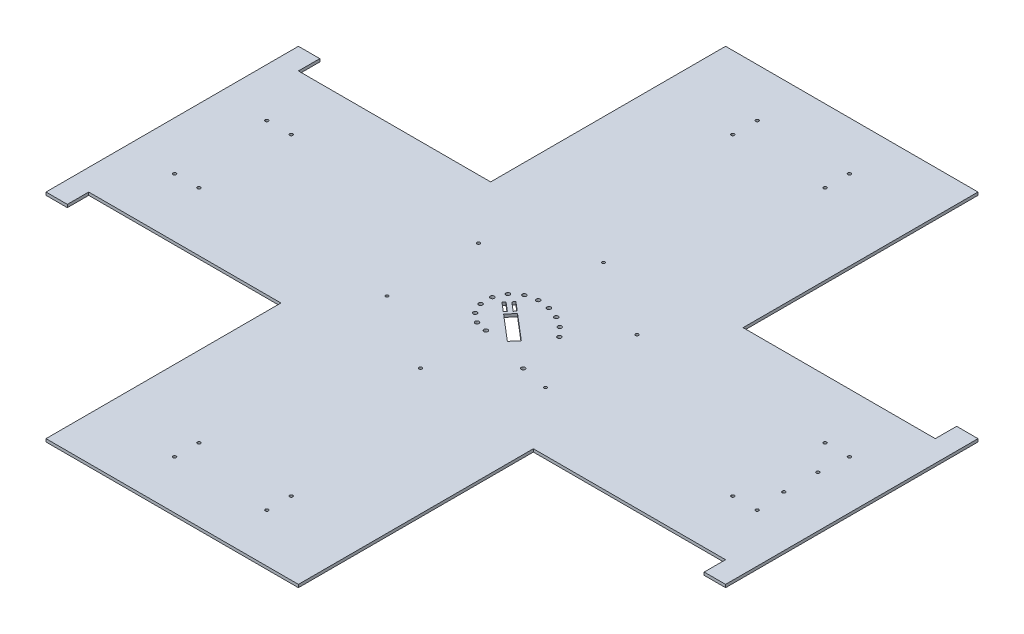
SolidWorks part; units mm, degrees
ref_plane "Front Plane" through (0, 0, 0) normal (0, 0, 1) x (1, 0, 0)
ref_plane "Top Plane" through (0, 0, 0) normal (0, 1, 0) x (1, 0, 0)
ref_plane "Right Plane" through (0, 0, 0) normal (1, 0, 0) x (0, 0, -1)
sketch "Sketch1" plane through (0, 0, 0) normal (0, 1, 0) x (1, 0, 0)
  line L0 (-350, -130) -> (-328, -130)
  line L1 (-130, -350) -> (130, -350)
  line L2 (-350, -130) -> (-350, 130)
  line L3 (-130, 350) -> (130, 350)
  line L4 (350, -130) -> (350, 130)
  line L7 (-350, 350) -> (-130, 350) construction
  line L8 (-350, 350) -> (-350, 130) construction
  line L9 (-350, 130) -> (-328, 130)
  line L10 (-130, 350) -> (-130, 130)
  line L11 (-350, 350) -> (-130, 130) construction
  line L12 (-350, 130) -> (-130, 350) construction
  line L13 (-350, -130) -> (-350, -350) construction
  line L14 (-350, -350) -> (-130, -350) construction
  line L15 (-130, -130) -> (-130, -350)
  line L16 (-350, -130) -> (-130, -350) construction
  line L17 (-350, -350) -> (-130, -130) construction
  line L18 (130, 350) -> (350, 350) construction
  line L19 (130, 350) -> (130, 130)
  line L20 (328, 130) -> (350, 130)
  line L21 (350, 350) -> (350, 130) construction
  line L22 (130, 350) -> (350, 130) construction
  line L23 (130, 130) -> (350, 350) construction
  line L24 (328, -130) -> (350, -130)
  line L25 (130, -130) -> (130, -350)
  line L26 (130, -350) -> (350, -350) construction
  line L27 (350, -130) -> (350, -350) construction
  line L28 (130, -130) -> (350, -350) construction
  line L29 (130, -350) -> (350, -130) construction
  line L30 (-328, -108) -> (-130, -108)
  line L31 (-328, 130) -> (-130, 130) construction
  line L32 (-328, 130) -> (-328, 108)
  line L33 (-328, 108) -> (-130, 108)
  line L34 (-130, 130) -> (-130, 108)
  line L35 (-328, 130) -> (-130, 108) construction
  line L36 (-328, 108) -> (-130, 130) construction
  line L37 (-328, -108) -> (-328, -130)
  line L38 (-328, -130) -> (-130, -130) construction
  line L39 (-130, -108) -> (-130, -130)
  line L40 (-328, -108) -> (-130, -130) construction
  line L41 (-328, -130) -> (-130, -108) construction
  line L42 (130, 130) -> (328, 130) construction
  line L43 (130, 130) -> (130, 108)
  line L44 (130, 108) -> (328, 108)
  line L45 (328, 130) -> (328, 108)
  line L46 (130, 130) -> (328, 108) construction
  line L47 (130, 108) -> (328, 130) construction
  line L48 (130, -108) -> (328, -108)
  line L49 (130, -108) -> (130, -130)
  line L50 (130, -130) -> (328, -130) construction
  line L51 (328, -108) -> (328, -130)
  line L52 (130, -108) -> (328, -130) construction
  line L53 (130, -130) -> (328, -108) construction
  line L54 (-130, 350) -> (130, -350) construction
  point P0 (0, 0)
  point P1 (0, 0)
  point P10 (-240, 240)
  point P15 (-240, -240)
  point P20 (240, 240)
  point P25 (240, -240)
  point P30 (-229, 119)
  point P35 (-229, -119)
  point P40 (229, 119)
  point P45 (229, -119)
  dimension "D3" = 220
  dimension "D4" = 220
  dimension "D5" = 220
  dimension "D6" = 220
  dimension "D7" = 220
  dimension "D8" = 220
  dimension "D9" = 220
  dimension "D10" = 220
  dimension "D11" = 22
  dimension "D12" = 198
  dimension "D13" = 22
  dimension "D14" = 198
  dimension "D15" = 22
  dimension "D16" = 198
  dimension "D17" = 22
  dimension "D18" = 198
extrude "Boss-Extrude1" add sketch "Sketch1" along normal blind 3
sketch "Sketch2" plane through (0, 3, 0) normal (0, 1, 0) x (1, 0, 0)
  line L0 (-300, 108) -> (-300, 47.5) construction
  line L1 (-130, 108) -> (-328, 108) construction
  line L2 (-300, -47.5) -> (-300, -108) construction
  line L3 (-328, -108) -> (-130, -108) construction
  line L4 (-300, 47.5) -> (-300, -47.5) construction
  line L5 (-47.5, 300) -> (-130, 300) construction
  line L6 (-130, 350) -> (-130, 108) construction
  line L7 (-47.5, 300) -> (47.5, 300) construction
  line L8 (47.5, 300) -> (130, 300) construction
  line L9 (130, 108) -> (130, 350) construction
  line L10 (130, 350) -> (-130, 350) construction
  line L11 (-350, 130) -> (-350, -130) construction
  line L12 (-130, -300) -> (-47.5, -300) construction
  line L13 (-130, -108) -> (-130, -350) construction
  line L14 (-47.5, -300) -> (47.5, -300) construction
  line L15 (47.5, -300) -> (130, -300) construction
  line L16 (130, -350) -> (130, -108) construction
  line L17 (-130, -350) -> (130, -350) construction
  line L18 (300, 108) -> (300, 47.5) construction
  line L19 (328, 108) -> (130, 108) construction
  line L20 (300, 47.5) -> (300, -47.5) construction
  line L21 (300, -47.5) -> (300, -108) construction
  line L22 (130, -108) -> (328, -108) construction
  line L23 (350, -130) -> (350, 130) construction
  line L24 (300, 47.5) -> (275, 47.5) construction
  line L25 (-47.5, -300) -> (-47.5, -275) construction
  line L26 (297.5, 17.5) -> (297.5, -17.5) construction
  circle A0 centre (-300, 47.5) radius 1.6
  circle A1 centre (-300, -47.5) radius 1.6
  circle A2 centre (-47.5, 300) radius 1.6
  circle A3 centre (47.5, 300) radius 1.6
  circle A4 centre (-47.5, -300) radius 1.6
  circle A5 centre (47.5, -300) radius 1.6
  circle A6 centre (300, 47.5) radius 1.6
  circle A7 centre (300, -47.5) radius 1.6
  circle A8 centre (-275, 47.5) radius 1.6
  circle A9 centre (-275, -47.5) radius 1.6
  circle A10 centre (-47.5, 275) radius 1.6
  circle A11 centre (47.5, 275) radius 1.6
  circle A12 centre (275, 47.5) radius 1.6
  circle A13 centre (275, -47.5) radius 1.6
  circle A14 centre (-47.5, -275) radius 1.6
  circle A15 centre (47.5, -275) radius 1.6
  circle A18 centre (297.5, 17.5) radius 1.6
  circle A19 centre (297.5, -17.5) radius 1.6
  point P73 (297.5, 0)
  point P74 (300, 0)
  dimension "D1" = 3.2
  dimension "D4" = 3.2
  dimension "D8" = 3.2
  dimension "D10" = 3.2
  dimension "D14" = 25
  dimension "D22" = 3.2
  dimension "D2" = 95
  dimension "D3" = 95
  dimension "D5" = 50
  dimension "D6" = 50
  dimension "D7" = 95
  dimension "D9" = 50
  dimension "D11" = 95
  dimension "D12" = 50
  dimension "D16" = 25
  dimension "D18" = 25
  dimension "D20" = 25
  dimension "D21" = 35
  dimension "D23" = 2.5
  dimension "D13" = 2
  dimension "D15" = 2
  dimension "D17" = 2
  dimension "D19" = 2
extrude "Cut-Extrude1" cut sketch "Sketch2" against normal through all
sketch "Sketch3" plane through (0, 3, 0) normal (0, 1, 0) x (1, 0, 0)
  line L0 (0, 27) -> (-11.6679, 24.3487) construction
  line L1 (-11.6679, 24.3487) -> (-21.0899, 16.8587) construction
  line L2 (-21.0899, 16.8587) -> (-26.3207, 6.0182) construction
  line L3 (-26.3207, 6.0182) -> (-26.3207, -6.0182) construction
  line L4 (-26.3207, -6.0182) -> (-21.0899, -16.8587) construction
  line L5 (-21.0899, -16.8587) -> (-11.6679, -24.3487) construction
  line L6 (-11.6679, -24.3487) -> (0.073, -26.9999) construction
  line L7 (0, 27) -> (12.5376, 25.5003) construction
  line L8 (12.5376, 25.5003) -> (24.3945, 21.1579) construction
  line L9 (24.3945, 21.1579) -> (34.9517, 14.2307) construction
  line L10 (34.9517, 14.2307) -> (43.655, 5.0823) construction
  line L11 (43.655, 5.0823) -> (53.1197, -41.5833) construction
  line L12 (0, 0) -> (0, 94.25) construction
  line L13 (0, 0) -> (0, 94.25) construction
  line L14 (0, 0) -> (81.6229, 47.125) construction
  line L16 (-5.4003, -3.2535) -> (20.8584, -25.6306)
  line L21 (20.8584, -25.6306) -> (27.4742, -17.8672)
  line L22 (-5.4003, -3.2535) -> (1.2156, 4.5099)
  line L23 (1.2156, 4.5099) -> (27.4742, -17.8672)
  line L31 (-7.6836, -1.3077) -> (-5.7378, 0.9757)
  line L32 (-5.7378, 0.9757) -> (-14.8712, 8.759)
  line L33 (-14.8712, 8.759) -> (-16.8171, 6.4757)
  line L34 (-16.8171, 6.4757) -> (-7.6836, -1.3077)
  line L35 (1.2156, 4.5099) -> (0, 0) construction
  line L36 (-3.0136, 4.1724) -> (-1.0678, 6.4558)
  line L37 (-1.0678, 6.4558) -> (-10.2012, 14.2391)
  line L38 (-10.2012, 14.2391) -> (-12.1471, 11.9557)
  line L39 (-12.1471, 11.9557) -> (-3.0136, 4.1724)
  line L41 (0, 0) -> (47.5952, 0) construction
  line L42 (0, 0) -> (0, -20) construction
  circle A0 centre (0, 27) radius 2
  circle A1 centre (12.5376, 25.5003) radius 2
  circle A2 centre (24.3945, 21.1579) radius 2
  circle A3 centre (34.9517, 14.2307) radius 2
  circle A4 centre (43.655, 5.0823) radius 2
  circle A5 centre (53.1197, -41.5833) radius 2
  circle A6 centre (0, 0) radius 135 construction
  circle A7 centre (-11.6679, 24.3487) radius 2
  circle A8 centre (-21.0899, 16.8587) radius 2
  circle A9 centre (-26.3207, 6.0182) radius 2
  circle A10 centre (-26.3207, -6.0182) radius 2
  circle A11 centre (-21.0899, -16.8587) radius 2
  circle A12 centre (-11.6679, -24.3487) radius 2
  circle A13 centre (0.073, -26.9999) radius 2
  circle A16 centre (0, 0) radius 27 construction
  circle A17 centre (0, 0) radius 28.4158 construction
  circle A18 centre (0, 0) radius 32.2916 construction
  circle A19 centre (0, 0) radius 37.7377 construction
  circle A20 centre (0, 0) radius 43.9498 construction
  circle A21 centre (0, 0) radius 67.4602 construction
  circle A22 centre (0, 0) radius 94.25 construction
  circle A23 centre (0, 94.25) radius 1.5
  circle A24 centre (81.6229, 47.125) radius 1.5
  circle A25 centre (81.6229, -47.125) radius 1.5
  circle A26 centre (0, -94.25) radius 1.5
  circle A27 centre (-81.6229, -47.125) radius 1.5
  circle A28 centre (-81.6229, 47.125) radius 1.5
  point P32 (0, 0)
  point P40 (0, 0)
  point P55 (13.7315, -11.8312)
  point P62 (0, 0)
  point P66 (0, 0)
  point P69 (0, 0)
  point P70 (0, 0)
  dimension "D1" = 4
  dimension "D2" = 34.5
  dimension "D3" = 270
  dimension "D4" = 54
  dimension "D6" = 1.4158
  dimension "D7" = 3.8759
  dimension "D8" = 5.4461
  dimension "D9" = 6.2121
  dimension "D10" = 23.5104
  dimension "D13" = 188.5
  dimension "D14" = 3
  dimension "D5" = 11.9653
  dimension "D11" = 12.627
  dimension "D12" = 47.6157
  dimension "D16" = 60
  dimension "D17" = 10.2
  dimension "D18" = 130.437
  dimension "D19" = 5.4003
  dimension "D20" = 12
  dimension "D21" = 3
  dimension "D22" = 3
  dimension "D23" = 4.6709
  dimension "D24" = 3
  dimension "D25" = 20
  dimension "D15" = 6
extrude "Cut-Extrude2" cut sketch "Sketch3" against normal through all
